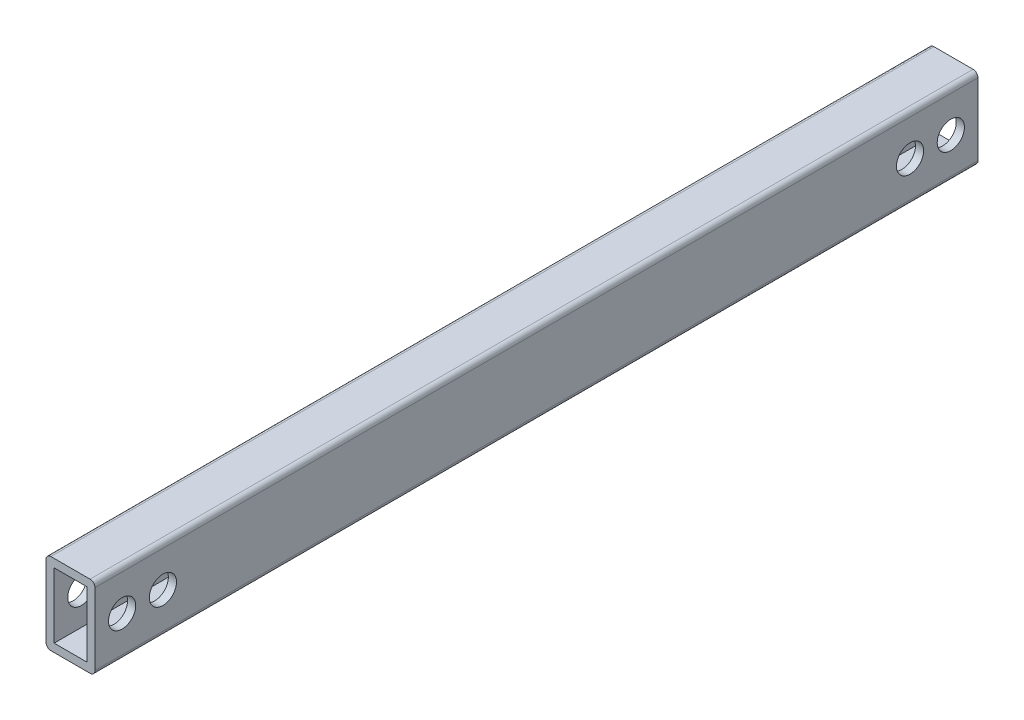
SolidWorks part; units mm, degrees
material "6061-T6 (SS)"
ref_plane "Front Plane" through (0, 0, 0) normal (0, 0, 1) x (1, 0, 0)
ref_plane "Top Plane" through (0, 0, 0) normal (0, 1, 0) x (1, 0, 0)
ref_plane "Right Plane" through (0, 0, 0) normal (1, 0, 0) x (0, 0, -1)
sketch "Sketch1" plane through (0, 0, 0) normal (0, 0, 1) x (1, 0, 0)
  line L1 (9, -15) -> (-9, -15)
  line L2 (9, -15) -> (9, 15)
  line L3 (9, 15) -> (-9, 15)
  line L4 (-9, -15) -> (-9, 15)
  line L5 (9, -15) -> (-9, 15) construction
  line L6 (9, 15) -> (-9, -15) construction
  line L7 (6, -12) -> (-6, -12)
  line L8 (6, -12) -> (6, 12)
  line L9 (6, 12) -> (-6, 12)
  line L10 (-6, -12) -> (-6, 12)
  line L11 (6, -12) -> (-6, 12) construction
  line L12 (6, 12) -> (-6, -12) construction
  point P0 (0, 0)
  point P6 (0, 0)
  dimension "D1" = 30
  dimension "D2" = 18
  dimension "D3" = 3
  dimension "D4" = 3
extrude "Body" add sketch "Sketch1" along normal blind 324.7986
sketch "Sketch2" plane through (9, 0, 0) normal (1, 0, 0) x (0, 0, -1)
  line L0 (0, 0) -> (-324.7986, 0) construction
  line L1 (-324.7986, -15) -> (-324.7986, 15) construction
  line L2 (-162.3993, -15) -> (-162.3993, 15) construction
  line L3 (-324.7986, -15) -> (0, -15) construction
  line L4 (-324.7986, 15) -> (0, 15) construction
  circle A0 centre (-314.7986, 0) radius 5
  circle A1 centre (-299.7986, 0) radius 5
  circle A2 centre (-25, 0) radius 5
  circle A3 centre (-10, 0) radius 5
  dimension "D1" = 10
  dimension "D2" = 10
  dimension "D3" = 10
  dimension "D4" = 15
extrude "Mount Holes" cut sketch "Sketch2" against normal through all
fillet "Corner Fillets" radius 1.8 4 edges at (-9, -15, 162.3993) (9, -15, 162.3993) (9, 15, 162.3993) (-9, 15, 162.3993)
equation "\"linkage_thickness\"= 18.0mm"
equation "\"width\"= 30.0mm"
equation "\"wall_thickness\"= 3.0mm"
equation "\"length\"= 324.79860433603017mm"
equation "\"angle\"= 5.580088106667777"
equation "\"bolt_diameter\"= 10.0mm"
equation "\"bolt_spacing\"= 5.0mm"
equation "\"D1@Sketch1\"=\"width\""
equation "\"D2@Sketch1\"=\"linkage_thickness\""
equation "\"D3@Sketch1\"=\"wall_thickness\""
equation "\"D4@Sketch1\"=\"wall_thickness\""
equation "\"D1@Body\"=\"length\""
equation "\"D1@Sketch2\"=\"bolt_diameter\""
equation "\"D2@Sketch2\"=\"bolt_diameter\""
equation "\"D3@Sketch2\"=\"bolt_spacing\"+\"bolt_diameter\"/2"
equation "\"D4@Sketch2\"=\"bolt_spacing\"+\"bolt_diameter\""
equation "\"D1@Corner Fillets\"=\"linkage_thickness\"/10"
